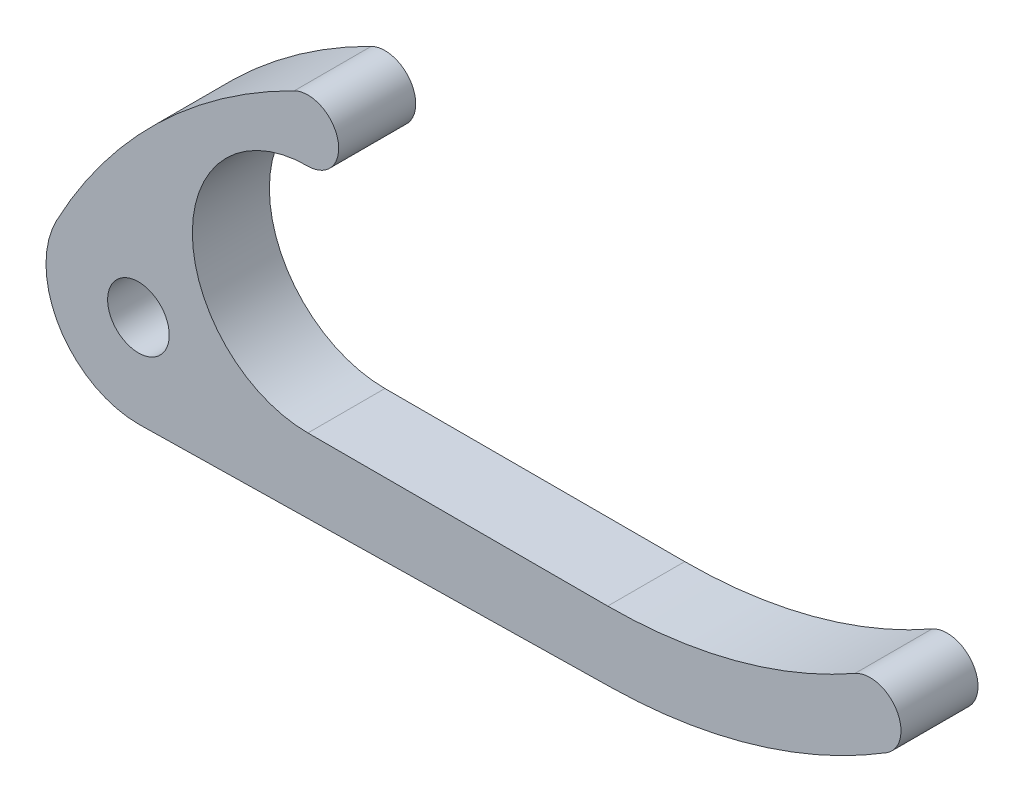
SolidWorks part; units mm, degrees
ref_plane "Front Plane" through (0, 0, 0) normal (0, 0, 1) x (1, 0, 0)
ref_plane "Top Plane" through (0, 0, 0) normal (0, 1, 0) x (1, 0, 0)
ref_plane "Right Plane" through (0, 0, 0) normal (1, 0, 0) x (0, 0, -1)
sketch "Sketch1" plane through (0, 0, 0) normal (0, 0, 1) x (1, 0, 0)
  line L0 (0, -12) -> (61.391, -10.9284)
  line L1 (22, -2) -> (60.9265, -2)
  line L2 (0.4188, -11.9927) -> (55.9066, -11.9927) construction
  circle A0 centre (0, 0) radius 4
  arc A1 (-10.6022, 5.6209) -> (0.4188, -11.9927) centre (0, 0) ccw
  arc A2 (22, 28) -> (20.2277, 35.5859) centre (22, 32) ccw
  arc A3 (20.2277, 35.5859) -> (-10.6022, 5.6209) centre (51.2438, -27.1676) ccw
  arc A4 (97.1109, -0.3976) -> (93.0247, 6.4783) centre (95, 3) ccw
  arc A5 (22, 28) -> (22, -2) centre (22, 13) ccw
  arc A6 (61.391, -10.9284) -> (97.1109, -0.3976) centre (60.1694, 59.0609) ccw
  arc A7 (60.9265, -2) -> (93.0247, 6.4783) centre (60.9265, 63) ccw
  point P3 (0, 0)
  dimension "D1" = 24
  dimension "D2" = 8
  dimension "D3" = 4
  dimension "D6" = 4
  dimension "D8" = 65
  dimension "D9" = 70
  dimension "D11" = 15
  dimension "D12" = 70
  dimension "D4" = 32
  dimension "D5" = 22
  dimension "D7" = 95
  dimension "D10" = 1
  dimension "D13" = 5
extrude "Boss-Extrude1" add sketch "Sketch1" along normal blind 10 contours A7 L1 A5 A2 A3 A1 L0 A6 A4 A0
